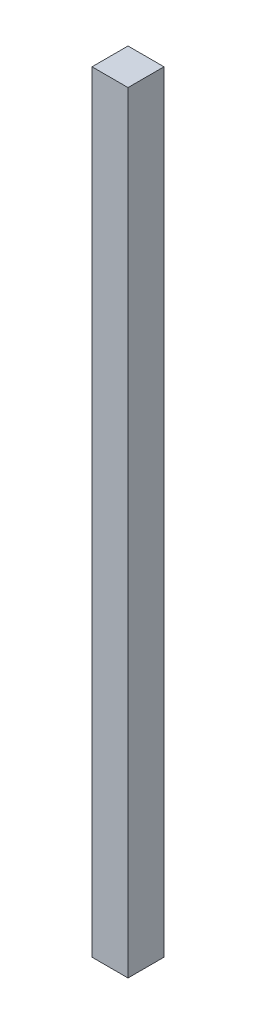
SolidWorks part; units mm, degrees
ref_plane "Ön Düzlem" through (0, 0, 0) normal (0, 0, 1) x (1, 0, 0)
ref_plane "Üst Düzlem" through (0, 0, 0) normal (0, 1, 0) x (1, 0, 0)
ref_plane "Sağ Düzlem" through (0, 0, 0) normal (1, 0, 0) x (0, 0, -1)
sketch "Sketch2" plane through (0, 0, 0) normal (0, 1, 0) x (1, 0, 0)
  line L1 (-24.5946, 16.2162) -> (45.4054, 16.2162)
  line L2 (-24.5946, 16.2162) -> (-24.5946, -53.7838)
  line L3 (-24.5946, -53.7838) -> (45.4054, -53.7838)
  line L4 (45.4054, 16.2162) -> (45.4054, -53.7838)
  dimension "D1" = 70
  dimension "D2" = 70
extrude "Boss-Extrude1" add sketch "Sketch2" along normal blind 1500
